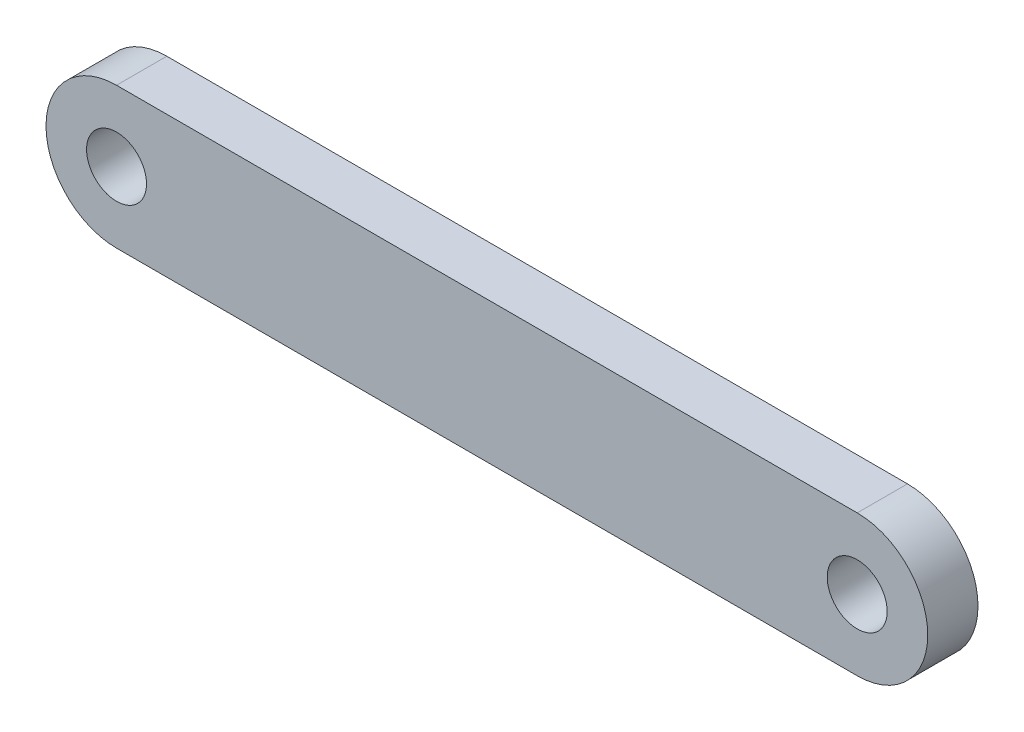
SolidWorks part; units mm, degrees
material "Pine"
ref_plane "Front" through (0, 0, 0) normal (0, 0, 1) x (1, 0, 0)
ref_plane "Top" through (0, 0, 0) normal (0, 1, 0) x (1, 0, 0)
ref_plane "Right" through (0, 0, 0) normal (1, 0, 0) x (0, 0, -1)
sketch "Sketch1" plane through (0, 0, 0) normal (0, 0, 1) x (1, 0, 0)
  line L1 (-25, 4) -> (25, 4)
  line L2 (-25, 4) -> (-25, -4)
  line L3 (-25, -4) -> (25, -4)
  line L4 (25, 4) -> (25, -4)
  line L5 (-25, 4) -> (25, -4) construction
  line L6 (-25, -4) -> (25, 4) construction
  point P0 (0, 0)
  dimension "D1" = 50
  dimension "D2" = 8
extrude "Boss-Extrude1" add sketch "Sketch1" along normal blind 2.85
sketch "Sketch2" plane through (0, 0, 2.85) normal (0, 0, 1) x (1, 0, 0)
  line L0 (21, -4) -> (26, -4)
  line L1 (26, -4) -> (26, 4)
  line L2 (26, 4) -> (21, 4)
  line L3 (25, -4) -> (25, 4) construction
  line L4 (25, 4) -> (-25, 4) construction
  line L5 (-25, -4) -> (25, -4) construction
  arc A0 (21, -4) -> (21, 4) centre (21, 0) ccw
  dimension "D1" = 1
extrude "Cut-Extrude1" cut sketch "Sketch2" against normal through all
sketch "Sketch3" plane through (0, 0, 2.85) normal (0, 0, 1) x (1, 0, 0)
  circle A0 centre (21, 0) radius 1.7
  dimension "D1" = 3.4
extrude "Cut-Extrude2" cut sketch "Sketch3" against normal through all
mirror "Mirror1" about plane through (0, 0, 0) normal (1, 0, 0) of "Cut-Extrude2", "Cut-Extrude1"
